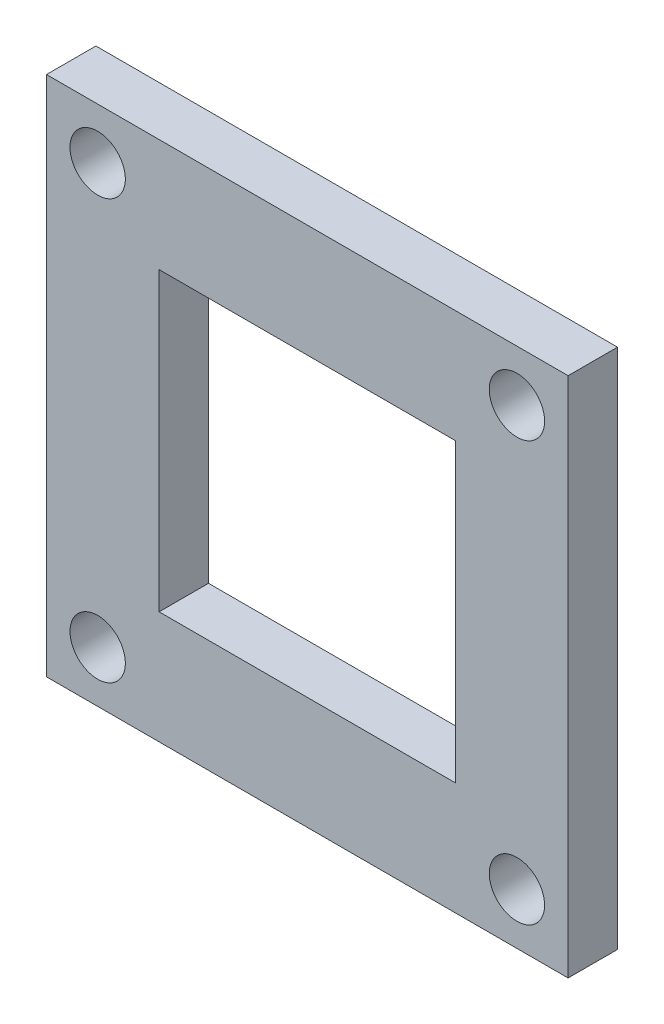
SolidWorks part; units mm, degrees
ref_plane "Front Plane" through (0, 0, 0) normal (0, 0, 1) x (1, 0, 0)
ref_plane "Top Plane" through (0, 0, 0) normal (0, 1, 0) x (1, 0, 0)
ref_plane "Right Plane" through (0, 0, 0) normal (1, 0, 0) x (0, 0, -1)
sketch "Sketch1" plane through (0, 0, 0) normal (0, 0, 1) x (1, 0, 0)
  line L1 (0, 0) -> (33.528, 0)
  line L2 (0, 0) -> (0, 33.528)
  line L3 (0, 33.528) -> (33.528, 33.528)
  line L4 (33.528, 0) -> (33.528, 33.528)
  dimension "D1" = 33.528
  dimension "D2" = 33.528
extrude "Boss-Extrude1" add sketch "Sketch1" along normal blind 3.175
sketch "Sketch2" plane through (0, 0, 3.175) normal (0, 0, 1) x (1, 0, 0)
  line L0 (33.528, 0) -> (33.528, 33.528) construction
  line L1 (7.239, 26.289) -> (26.289, 26.289)
  line L2 (7.239, 26.289) -> (7.239, 7.239)
  line L3 (7.239, 7.239) -> (26.289, 7.239)
  line L4 (26.289, 26.289) -> (26.289, 7.239)
  line L5 (0, 0) -> (33.528, 0) construction
  dimension "D1" = 19.05
  dimension "D2" = 19.05
  dimension "D3" = 7.239
  dimension "D4" = 7.239
extrude "Cut-Extrude1" cut sketch "Sketch2" against normal blind 3.175
sketch "Sketch3" plane through (0, 0, 3.175) normal (0, 0, 1) x (1, 0, 0)
  line L3 (0, 0) -> (33.528, 0) construction
  line L4 (33.528, 0) -> (33.528, 33.528) construction
  line L5 (16.764, 33.528) -> (16.764, 0) construction
  line L6 (33.528, 33.528) -> (0, 33.528) construction
  circle A0 centre (30.2387, 30.2387) radius 1.778
  circle A1 centre (30.2387, 3.2893) radius 1.778
  circle A2 centre (3.2893, 3.2893) radius 1.778
  circle A3 centre (3.2893, 30.2387) radius 1.778
  dimension "D1" = 3.556
  dimension "D2" = 26.9494
  dimension "D3" = 3.2893
  dimension "D4" = 3.556
  dimension "D5" = 3.2893
  dimension "D6" = 3.2893
extrude "Cut-Extrude2" cut sketch "Sketch3" against normal blind 3.175
